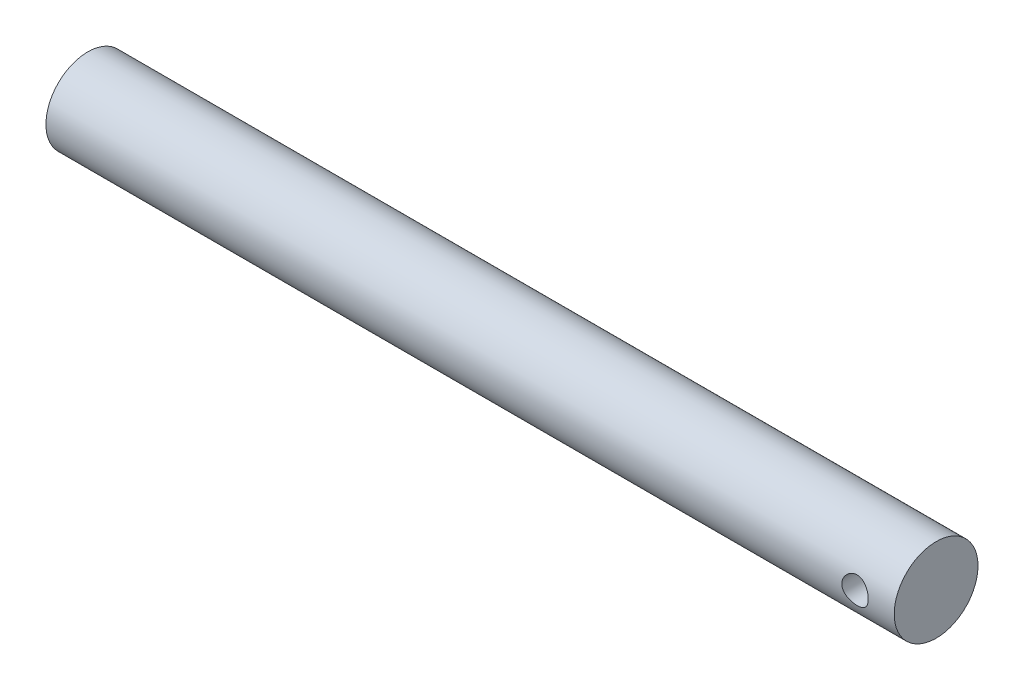
SolidWorks part; units mm, degrees
ref_plane "Front Plane" through (0, 0, 0) normal (0, 0, 1) x (1, 0, 0)
ref_plane "Top Plane" through (0, 0, 0) normal (0, 1, 0) x (1, 0, 0)
ref_plane "Right Plane" through (0, 0, 0) normal (1, 0, 0) x (0, 0, -1)
sketch "Sketch1" plane through (0, 0, 0) normal (1, 0, 0) x (0, 0, -1)
  circle A0 centre (0, 0) radius 10.033
  dimension "D1" = 20.066
extrude "Boss-Extrude1" add sketch "Sketch1" along normal blind 203.2
sketch "Sketch2" plane through (0, 0, 0) normal (0, 0, 1) x (1, 0, 0)
  line L0 (203.2, 0) -> (193.802, 0) construction
  line L1 (203.2, -10.033) -> (203.2, 10.033) construction
  circle A0 centre (193.802, 0) radius 3.175
  dimension "D2" = 6.35
  dimension "D1" = 9.398
extrude "Cut-Extrude1" cut sketch "Sketch2" against normal mid plane 25.4
